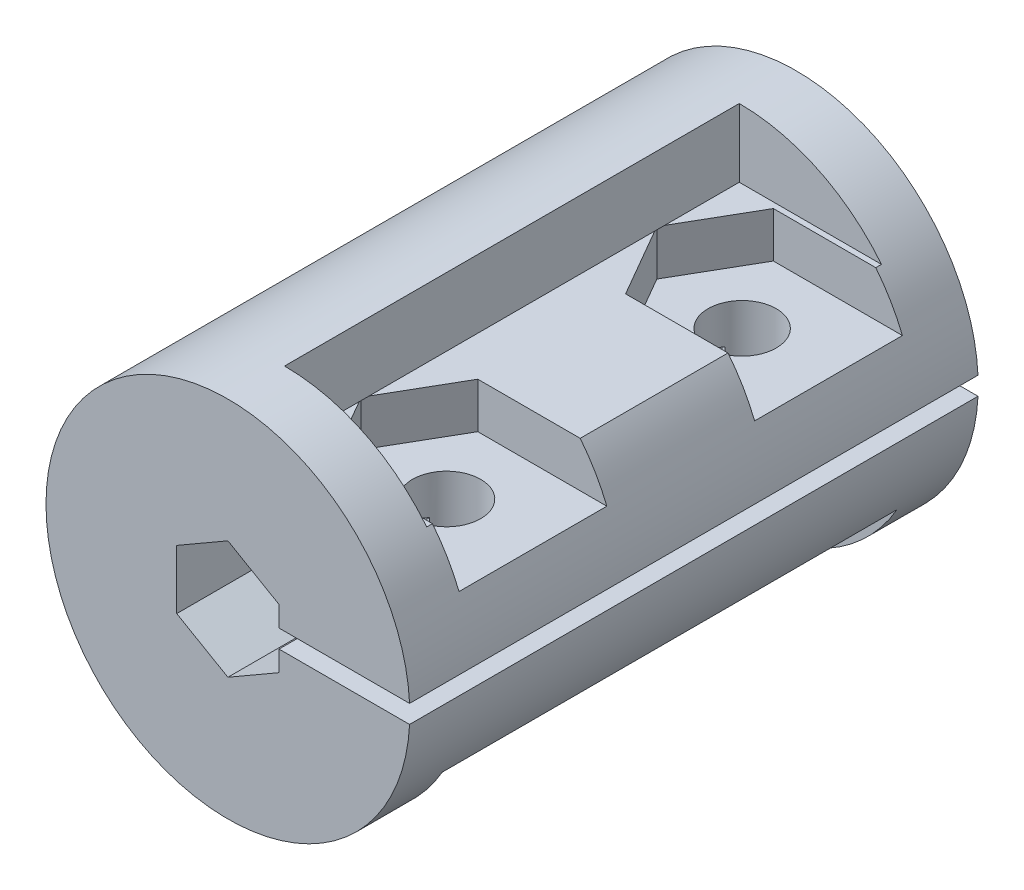
SolidWorks part; units mm, degrees
ref_plane "Plano frontal" through (0, 0, 0) normal (0, 0, 1) x (1, 0, 0)
ref_plane "Plano superior" through (0, 0, 0) normal (0, 1, 0) x (1, 0, 0)
ref_plane "Plano direito" through (0, 0, 0) normal (1, 0, 0) x (0, 0, -1)
sketch "Esboço1" plane through (0, 0, 0) normal (0, 0, 1) x (1, 0, 0)
  line L7 (2.25, -0.4) -> (5.9867, -0.4)
  line L9 (2.25, 0.4) -> (5.9867, 0.4)
  line L10 (2.25, 0.4) -> (2.25, 1.299)
  line L11 (0, 2.5981) -> (-2.25, 1.299)
  line L12 (-2.25, 1.299) -> (-2.25, -1.299)
  line L13 (-2.25, -1.299) -> (0, -2.5981)
  line L14 (0, -2.5981) -> (2.25, -1.299)
  line L15 (2.25, -1.299) -> (2.25, -0.4)
  line L16 (2.25, 1.299) -> (0, 2.5981)
  line L17 (5.9867, 0.4) -> (7.99, 0.4)
  line L18 (5.9867, -0.4) -> (7.99, -0.4)
  circle A1 centre (0, 0) radius 2.25 construction
  arc A2 (7.99, 0.4) -> (7.99, -0.4) centre (0, 0) ccw
extrude "Ressalto-extrusão2" add sketch "Esboço1" along normal blind 25
ref_plane "Plano2" through (0, 8, 0) normal (0, 1, 0) x (1, 0, 0)
sketch "Esboço3" plane through (0, 8, 0) normal (0, 1, 0) x (1, 0, 0)
  line L0 (7.99, -2.5) -> (7.99, -22.5)
  line L9 (7.99, -22.5) -> (0.99, -22.5)
  line L10 (7.99, -2.5) -> (0.99, -2.5)
  line L12 (0.99, -2.5) -> (0.99, -22.5)
extrude "Corte-extrusão1" cut sketch "Esboço3" against normal blind 3
ref_plane "Plano3" through (0, -8, 0) normal (0, 1, 0) x (1, 0, 0)
sketch "Esboço4" plane through (0, -8, 0) normal (0, 1, 0) x (1, 0, 0)
  line L0 (0.99, -2.5) -> (10.9749, -2.5)
  line L1 (10.9749, -2.5) -> (10.9749, -22.5)
  line L2 (0.99, -2.5) -> (0.99, -22.5)
  line L3 (0.99, -22.5) -> (10.9749, -22.5)
extrude "Corte-extrusão2" cut sketch "Esboço4" along normal blind 4
sketch "Esboço5" plane through (0, -8, 0) normal (0, 1, 0) x (1, 0, 0)
  circle A1 centre (3.6175, -6) radius 1.5
  circle A2 centre (3.6175, -19) radius 1.5
extrude "Corte-extrusão7" cut sketch "Esboço5" along normal through all
sketch "Esboço11" plane through (0, 8, 0) normal (0, 1, 0) x (1, 0, 0)
  line L0 (0.99, -2.5) -> (0.49, -2.5)
  line L1 (0.49, -2.5) -> (0.49, -22.5)
  line L2 (0.99, -22.5) -> (0.49, -22.5)
  line L3 (0.99, -22.5) -> (12.0599, -22.5)
  line L4 (12.0599, -22.5) -> (12.0599, -2.5)
  line L5 (0.99, -2.5) -> (12.0599, -2.5)
extrude "Corte-extrusão8" cut sketch "Esboço11" against normal blind 3
sketch "Esboço12" plane through (0, 5, 0) normal (0, 1, 0) x (1, 0, 0)
  line L0 (5.4939, -9.25) -> (10.4927, -9.25)
  line L2 (5.4939, -2.75) -> (1.7411, -2.75)
  line L3 (1.7411, -2.75) -> (-0.1353, -6)
  line L4 (-0.1353, -6) -> (1.7411, -9.25)
  line L5 (1.7411, -9.25) -> (5.4939, -9.25)
  line L8 (5.4939, -15.75) -> (1.7411, -15.75)
  line L9 (1.7411, -15.75) -> (-0.1353, -19)
  line L10 (-0.1353, -19) -> (1.7411, -22.25)
  line L11 (1.7411, -22.25) -> (5.4939, -22.25)
  line L13 (5.4939, -2.75) -> (10.4927, -2.75)
  line L14 (5.4939, -22.25) -> (10.4927, -22.25)
  line L15 (5.4939, -15.75) -> (10.4927, -15.75)
  line L16 (10.4927, -22.25) -> (10.4927, -15.75)
  line L17 (10.4927, -9.25) -> (10.4927, -2.75)
  line L18 (6.4321, -17.375) -> (5.4939, -15.75) [skipped]
  line L19 (5.4939, -22.25) -> (6.4321, -20.625) [skipped]
  line L20 (6.4321, -4.375) -> (5.4939, -2.75) [skipped]
  line L21 (5.4939, -9.25) -> (6.4321, -7.625) [skipped]
  circle A0 centre (3.6175, -6) radius 3.25 construction
  circle A1 centre (3.6175, -19) radius 3.25 construction
extrude "Corte-extrusão9" cut sketch "Esboço12" against normal blind 2
sketch "Esboço13" plane through (0, 8, 0) normal (0, 1, 0) x (1, 0, 0)
  line L0 (0.49, -2.5) -> (-0.01, -2.5)
  line L1 (-0.01, -2.5) -> (-0.01, -22.5)
  line L2 (0.49, -22.5) -> (-0.01, -22.5)
  line L3 (0.49, -22.5) -> (15.4811, -22.5)
  line L4 (15.4811, -22.5) -> (15.4811, -2.5)
  line L5 (0.49, -2.5) -> (15.4811, -2.5)
extrude "Corte-extrusão11" cut sketch "Esboço13" against normal blind 3
ref_plane "Plano4" through (0, 0, 12.5) normal (0, 0, 1) x (1, 0, 0)
sketch "Esboço14" plane through (0, 0, 12.5) normal (0, 0, 1) x (1, 0, 0)
  line L1 (-1.85, 1.0681) -> (-1.85, -1.0681)
  line L2 (-1.85, -1.0681) -> (0, -2.1362)
  line L3 (0, -2.1362) -> (1.45, -1.299)
  line L5 (1.45, 1.299) -> (0, 2.1362)
  line L6 (0, 2.1362) -> (-1.85, 1.0681)
  line L7 (-2.25, 1.299) -> (-2.25, -1.299)
  line L8 (-2.25, -1.299) -> (0, -2.5981)
  line L9 (0, -2.5981) -> (2.25, -1.299)
  line L11 (2.25, 1.299) -> (0, 2.5981)
  line L12 (0, 2.5981) -> (-2.25, 1.299)
  line L17 (2.25, 1.299) -> (1.45, 1.299)
  line L18 (2.25, -1.299) -> (1.45, -1.299)
  line L20 (2.25, -1.299) -> (2.25, -0.4) [skipped]
  line L21 (1.85, -1.1547) -> (1.85, -1.0308) [skipped]
  line L22 (-1.85, 1.0681) -> (-1.85, -1.0681)
  line L23 (-1.85, -1.0681) -> (0, -2.1362)
  line L24 (0, -2.1362) -> (1.45, -1.299)
  line L26 (1.45, 1.299) -> (0, 2.1362)
  line L27 (0, 2.1362) -> (-1.85, 1.0681)
  line L28 (1.85, -1.0681) -> (1.85, 0) [skipped]
  circle A0 centre (0, 0) radius 1.85 construction
  circle A1 centre (0, 0) radius 2.25 construction
  circle A2 centre (0, 0) radius 1.85 construction
extrude "Ressalto-extrusão4" add sketch "Esboço14" along normal mid plane 14 contours L9 L18 L3 L2 L1 L6 L5 L17 L11 L12 L7 L8
